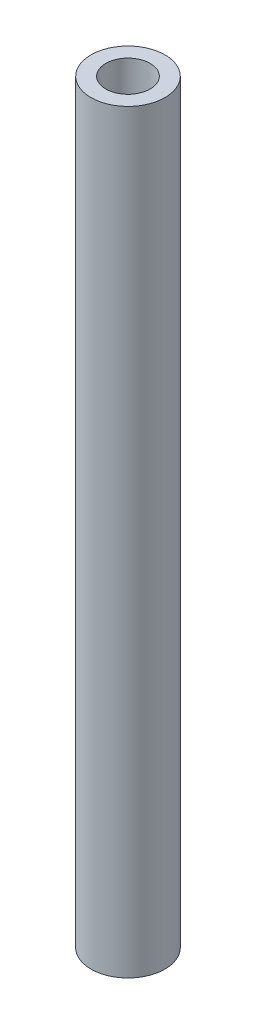
SolidWorks part; units mm, degrees
ref_plane "Front Plane" through (0, 0, 0) normal (0, 0, 1) x (1, 0, 0)
ref_plane "Top Plane" through (0, 0, 0) normal (0, 1, 0) x (1, 0, 0)
ref_plane "Right Plane" through (0, 0, 0) normal (1, 0, 0) x (0, 0, -1)
sketch "Sketch1" plane through (0, 0, 0) normal (0, 1, 0) x (1, 0, 0)
  circle A0 centre (0, 0) radius 2.5
  circle A1 centre (0, 0) radius 1.5
  dimension "D1" = 3
  dimension "D2" = 5
extrude "Boss-Extrude1" add sketch "Sketch1" along normal blind 51
